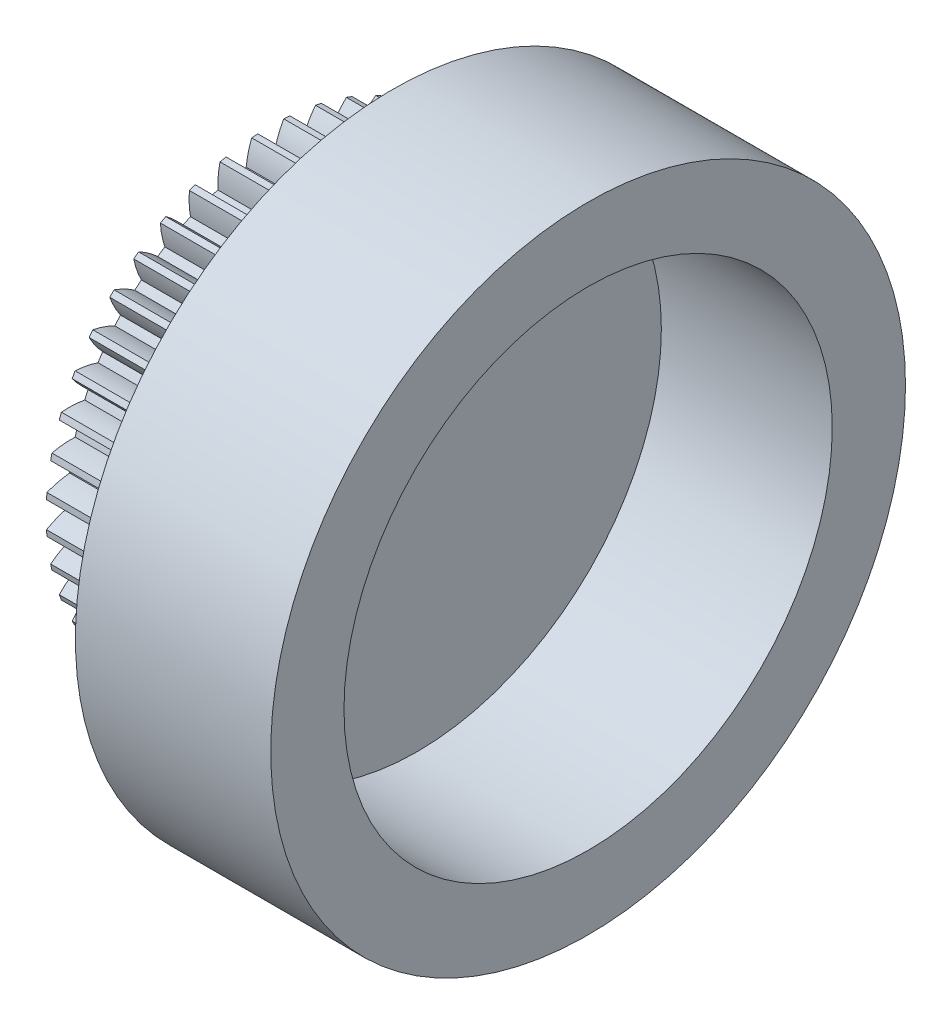
SolidWorks part; units mm, degrees
ref_plane "Plane1" through (0, 0, 0) normal (0, 0, 1) x (1, 0, 0)
ref_plane "Plane2" through (0, 0, 0) normal (0, 1, 0) x (1, 0, 0)
ref_plane "Plane3" through (0, 0, 0) normal (1, 0, 0) x (0, 0, -1)
sketch "HoldingSke" plane through (0, 0, 0) normal (0, 1, 0) x (1, 0, 0)
  line L0 (0, 0) -> (1.7983, -1.7366)
  line L1 (-15, 0) -> (100, 0) construction
  line L2 (0, 0) -> (-2.1039, 2.3779)
  line L3 (0, 0) -> (-11.863, 4.5341)
  line L4 (0, 0) -> (6.2122, 5.9991)
  line L5 (0, 0) -> (-46.8476, -17.4728)
  line L6 (0, 0) -> (-4.1448, -2.7965)
  line L7 (-2.1039, 2.3779) -> (8.6586, 51.2059)
  line L8 (-76.2, 54.61) -> (-73.9, 54.61)
  line L9 (-71.009, 38.7566) -> (-53.1078, 45.2721)
  line L10 (-76.2, 71.12) -> (104.1128, 71.12)
  line L11 (0, 0) -> (-5, 0)
  line L12 (-76.2, 101.6) -> (-76.185, 101.6)
  line L13 (24.9733, 27.94) -> (52.9518, 28.4284)
  line L14 (24.9733, 27.94) -> (24.9743, 27.94)
  line L15 (24.9733, 27.94) -> (100.4006, 29.5858)
  line L16 (-63.627, -0.4) -> (-12.827, -0.4)
  circle A0 centre (0, 0) radius 7.5
  circle A1 centre (0, 0) radius 8.299
  circle A2 centre (0, 0) radius 37.5
  circle A3 centre (0, 0) radius 7.5
  dimension "MHD" = 16.598
  dimension "Hub_dia" = 75
  dimension "Bore" = 15
  dimension "MBD" = 15
  dimension "Num_teeth" = 44
  dimension "Pitch" = 2.5
  dimension "Overall_len" = 50
  dimension "Show_teeth" = 44
  dimension "Thickness" = 5
  dimension "OAL" = 50.0001
  dimension "T_dim" = 2.3
  dimension "Ap" = 20
  dimension "H" = 19.05
  dimension "Pitch_radius" = 180.3128
  dimension "Width" = 5
  dimension "Backlash" = 0.015
  dimension "Addendum_fac" = 1
  dimension "Dedendum_fac" = 1.25
  dimension "Clearance_fac" = 0.25
  dimension "Dedendum_add" = 0.001
  dimension "Module" = 0.4
sketch "BasProSke" plane through (0, 0, 0) normal (0, 1, 0) x (1, 0, 0)
  line L0 (-10, 0) -> (60, 0) construction
  line L1 (0, 0) -> (0, 9.2)
  line L2 (0, 0) -> (5, 0)
  line L3 (5, 0) -> (5, 9.2)
  line L4 (5, 9.2) -> (0, 9.2)
  dimension "Thickness" = 5
  dimension "Diameter" = 18.4
revolve "Base-Revolve" add sketch "BasProSke" angle 360 about L0
sketch "TooCutSke" plane through (0, 0, 0) normal (1, 0, 0) x (0, 0, -1)
  line L1 (0, 0) -> (0, 107) construction
  line L2 (0, 0) -> (-0.3403, 8.7934) construction
  line L3 (0, 0) -> (-1.2549, 17.5458) construction
  line L4 (-0.3403, 8.7934) -> (-0.6274, 8.7729) construction
  arc A0 (0.177, 8.2971) -> (-0.177, 8.2971) centre (0, 0) ccw
  arc A1 (0.5454, 9.2093) -> (-0.5454, 9.2093) centre (0, 0) ccw
  circle A2 centre (0, 0) radius 8.8 construction
  circle A3 centre (0, 0) radius 8.2693 construction
  arc A4 (-0.177, 8.2971) -> (-0.5454, 9.2093) centre (-3.593, 7.4479) ccw
  arc A5 (0.5454, 9.2093) -> (0.177, 8.2971) centre (3.593, 7.4479) ccw
  dimension "Root_dia" = 16.598
  dimension "Overcut_dia" = 18.4508
  dimension "Pitch_dia" = 17.6
  dimension "Base_dia" = 16.5386
  dimension "Flank_rad" = 3.52
  dimension "Half_ang" = 4.091
  dimension "Half_CT" = 0.2878
extrude "ToothCut" cut sketch "TooCutSke" along normal through all
fillet "Breaks" [suppressed] radius 0.008
fillet "RootFillets" [suppressed] radius 0.101
pattern_circular "TeethCuts" count 44 every 8.182 about axis through (-10, 0, 0) along (1, 0, 0) of "ToothCut", "RootFillets", "Breaks"
sketch "HubNeaOneSke" plane through (0, 0, 0) normal (-1, 0, 0) x (0, 0, 1)
  circle A0 centre (0, 0) radius 8.299
  dimension "Diameter" = 16.598
extrude "HubNearOne" [suppressed] add sketch "HubNeaOneSke" along normal blind 45.0001
sketch "HubNeaBotSke" plane through (0, 0, 0) normal (-1, 0, 0) x (0, 0, 1)
  circle A0 centre (0, 0) radius 8.299
  dimension "Diameter" = 16.598
extrude "HubNearBoth" [suppressed] add sketch "HubNeaBotSke" along normal blind 22.5
ref_plane "FarPln" through (5, 0, 0) normal (1, 0, 0) x (0, 0, -1)
sketch "HubFarSke" plane through (5, 0, 0) normal (1, 0, 0) x (0, 0, -1)
  circle A0 centre (0, 0) radius 8.299
  dimension "Diameter" = 16.598
extrude "HubFar" [suppressed] add sketch "HubFarSke" along normal blind 22.5
sketch "BorSke" plane through (0, 0, 0) normal (1, 0, 0) x (0, 0, -1)
  circle A0 centre (0, 0) radius 7.5
  dimension "Diameter" = 15
extrude "Bore" cut sketch "BorSke" along normal mid plane 100.0001
sketch "KeySke" plane through (0, 0, 0) normal (1, 0, 0) x (0, 0, -1)
  line L0 (-2.5, 0) -> (-2.5, 9.8)
  line L1 (-2.5, 9.8) -> (2.5, 9.8)
  line L2 (2.5, 9.8) -> (2.5, 0)
  line L3 (0, 0) -> (0, 34) construction
  line L4 (-2.5, 0) -> (2.5, 0)
  dimension "Width" = 5
  dimension "Offset" = 9.8
extrude "Keyway" [suppressed] cut sketch "KeySke" along normal mid plane 100.0001
pattern_circular "Keyway2" [suppressed] count 2 every 90 about axis through (-10, 0, 0) along (1, 0, 0)
sketch "Sketch1" plane through (5, 0, 0) normal (1, 0, 0) x (0, 0, -1)
  circle A0 centre (0, 0) radius 10
  circle A1 centre (0, 0) radius 13
  dimension "D1" = 20
  dimension "D2" = 3
extrude "Boss-Extrude1" add sketch "Sketch1" along normal blind 1 contours A0 | A1 A0
sketch "Sketch2" plane through (6, 0, 0) normal (1, 0, 0) x (0, 0, -1)
  circle A0 centre (0, 0) radius 10 construction
  circle A1 centre (0, 0) radius 13 construction
  circle A2 centre (0, 0) radius 10
  circle A3 centre (0, 0) radius 13
extrude "Boss-Extrude2" add sketch "Sketch2" along normal blind 7
sketch "Sketch3" plane through (6, 0, 0) normal (1, 0, 0) x (0, 0, -1)
  circle A0 centre (0, 0) radius 4
  dimension "D1" = 8
equation "' \"Module@HoldingSke\" = 6.35"
equation "' \"Num_teeth@HoldingSke\" = 12"
equation "' \"Ap@HoldingSke\" =  20"
equation "' \"Ap@HoldingSke\" = 20"
equation "' \"Width@HoldingSke\" = 0.5 * 25.4"
equation "' \"Hub_dia@HoldingSke\"= 1 * 25.4"
equation "' \"Hub_dia@HoldingSke\" = 1 * 25.4"
equation "' \"Overall_len@HoldingSke\" = 1.0 * 25.4"
equation "' \"Bore@HoldingSke\" = 0.75 * 25.4"
equation "' \"T_dim@HoldingSke\" = 0.1 * 25.4"
equation "' \"Width@KeySke\" = 0.25 * 25.4"
equation "' \"Show_teeth@HoldingSke\" = 13"
equation "' \"Backlash@HoldingSke\" = 0.009 * 25.4"
equation "' \"Addendum_fac@HoldingSke\" = 1.0"
equation "' \"Dedendum_fac@HoldingSke\" = 1.25"
equation "' \"Dedendum_add@HoldingSke\" = 0.00005 * 25.4"
equation "' \"Clearance_fac@HoldingSke\" = 0.25"
equation "\"Pitch@HoldingSke\" = 1 / \"Module@HoldingSke\""
equation "\"Overcut_dia@TooCutSke\" = (\"Num_teeth@HoldingSke\" + 2 * \"Addendum_fac@HoldingSke\") / \"Pitch@HoldingSke\" + 0.002 * 25.4"
equation "\"Pitch_dia@TooCutSke\" = \"Num_teeth@HoldingSke\" / \"Pitch@HoldingSke\""
equation "\"Base_dia@TooCutSke\" = \"Num_teeth@HoldingSke\" / \"Pitch@HoldingSke\" * cos((\"Ap@HoldingSke\"  * 3.14159265 / 180))"
equation "\"Root_dia@TooCutSke\" = (\"Num_teeth@HoldingSke\" + 2) / \"Pitch@HoldingSke\" - 2 * (\"Addendum_fac@HoldingSke\" + \"Dedendum_fac@HoldingSke\") / \"Pitch@HoldingSke\" - \"Dedendum_add@HoldingSke\" * 2"
equation "\"Half_ang@TooCutSke\" = 180 / \"Num_teeth@HoldingSke\""
equation "\"Half_CT@TooCutSke\" = \"Num_teeth@HoldingSke\" / \"Pitch@HoldingSke\" * sin((3.14159265 / 2 / \"Num_teeth@HoldingSke\")) / 2 - 7 * \"Backlash@HoldingSke\" / 4"
equation "\"Flank_rad@TooCutSke\" = \"Num_teeth@HoldingSke\" / \"Pitch@HoldingSke\" / 5"
equation "\"Radius@RootFillets\" = \"Clearance_fac@HoldingSke\" / \"Pitch@HoldingSke\" + \"Dedendum_add@HoldingSke\""
equation "\"Break_rad@Breaks\" = 0.02 / \"Pitch@HoldingSke\""
equation "\"Thickness@HoldingSke\" = \"Width@HoldingSke\""
equation "\"OAL@HoldingSke\" = \"Thickness@HoldingSke\""
equation "\"MHD@HoldingSke\" = (\"Num_teeth@HoldingSke\" + 2) / \"Pitch@HoldingSke\" - 2 * (\"Addendum_fac@HoldingSke\" + \"Dedendum_fac@HoldingSke\")  / \"Pitch@HoldingSke\" - \"Dedendum_add@HoldingSke\" * 2"
equation "\"MBD@HoldingSke\" = (\"Num_teeth@HoldingSke\" + 2) / \"Pitch@HoldingSke\" - 2 * (\"Addendum_fac@HoldingSke\" + \"Dedendum_fac@HoldingSke\")  / \"Pitch@HoldingSke\" - \"Dedendum_add@HoldingSke\" * 2 - 0.002 * 25.4"
equation "\"MHD@HoldingSke\" = ((sgn( \"MHD@HoldingSke\" - \"Hub_dia@HoldingSke\" )-1)*( \"MHD@HoldingSke\" - \"Hub_dia@HoldingSke\" ))/-2+ \"Hub_dia@HoldingSke\""
equation "\"MBD@HoldingSke\" = ((sgn( \"MBD@HoldingSke\" - \"Bore@HoldingSke\" )-1)*( \"MBD@HoldingSke\" - \"Bore@HoldingSke\" ))/-2+ \"Bore@HoldingSke\""
equation "\"OAL@HoldingSke\" = ((sgn( \"OAL@HoldingSke\" - \"Overall_len@HoldingSke\" )+1)*( \"OAL@HoldingSke\" - \"Overall_len@HoldingSke\" ))/2 + \"Overall_len@HoldingSke\" + 0.000002 * 25.4"
equation "\"Num_teeth@TeethCuts\" = int( \"Show_teeth@HoldingSke\" ) + 1"
equation "\"Num_teeth@TeethCuts\" = ((sgn( \"Num_teeth@TeethCuts\" - \"Num_teeth@HoldingSke\" )-1)*( \"Num_teeth@TeethCuts\" - \"Num_teeth@HoldingSke\" ))/-2+ \"Num_teeth@HoldingSke\""
equation "\"Num_teeth@TeethCuts\" = ((sgn( \"Num_teeth@TeethCuts\" - 2.0)+1)*( \"Num_teeth@TeethCuts\" - 2.0))/2 +2.0"
equation "\"Angle@TeethCuts\" = 360.0 / \"Num_teeth@HoldingSke\""
equation "\"Diameter@BasProSke\" = (\"Num_teeth@HoldingSke\" + 2 * \"Addendum_fac@HoldingSke\") / \"Pitch@HoldingSke\""
equation "\"Thickness@BasProSke\"  = \"Thickness@HoldingSke\""
equation "' \"Fillet_rad@BasProSke\" =  \"Thickness@HoldingSke\" * 0.05"
equation "' \"Fillet_rad@BasProSke\" = \"Thickness@HoldingSke\" * 0.05"
equation "\"MHD@HoldingSke\" = ((sgn( \"MHD@HoldingSke\" - \"Root_dia@TooCutSke\" )-1)*( \"MHD@HoldingSke\" - \"Root_dia@TooCutSke\" ))/-2+ \"Root_dia@TooCutSke\""
equation "\"Diameter@HubNeaOneSke\" = \"MHD@HoldingSke\""
equation "\"Length@HubNearOne\" = \"OAL@HoldingSke\" - \"Thickness@BasProSke\""
equation "\"Diameter@HubNeaBotSke\" = \"MHD@HoldingSke\""
equation "\"Length@HubNearBoth\" = ( \"OAL@HoldingSke\" - \"Thickness@BasProSke\" ) / 2.0"
equation "\"Thickness@FarPln\" = \"Thickness@BasProSke\""
equation "\"Diameter@HubFarSke\" = \"MHD@HoldingSke\""
equation "\"Length@HubFar\" = ( \"OAL@HoldingSke\" - \"Thickness@BasProSke\" ) / 2.0"
equation "\"Diameter@BorSke\" = \"MBD@HoldingSke\""
equation "\"D1@Bore\" = \"OAL@HoldingSke\" * 2.0"
equation "\"D1@Keyway\" = \"OAL@HoldingSke\" * 2.0"
equation "\"Offset@KeySke\" = \"T_dim@HoldingSke\" + \"MBD@HoldingSke\" / 2.0"
